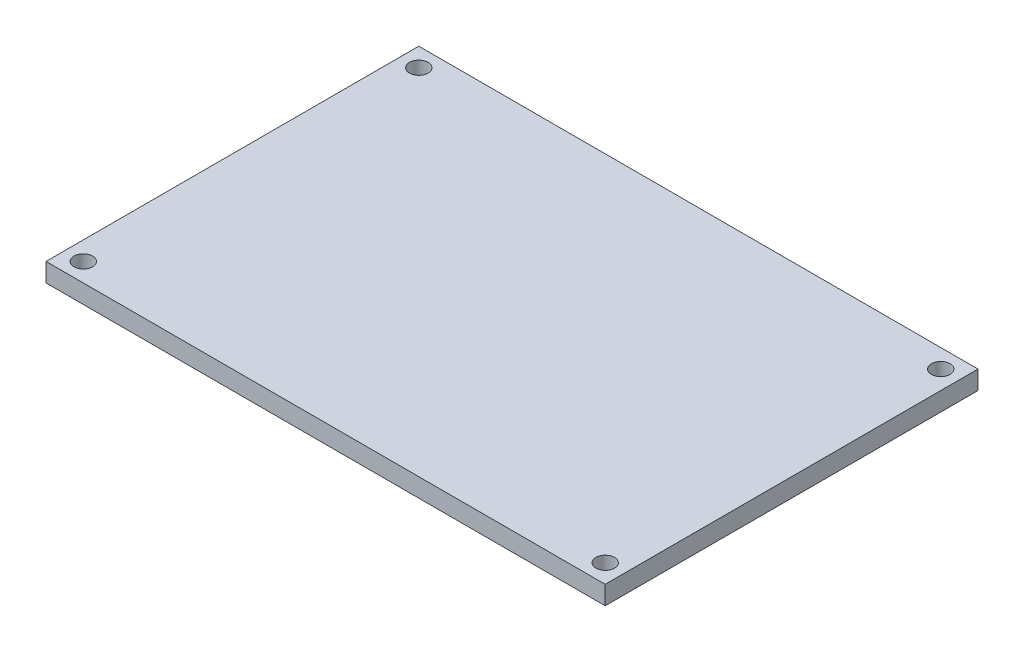
SolidWorks part; units mm, degrees
ref_plane "Front Plane" through (0, 0, 0) normal (0, 0, 1) x (1, 0, 0)
ref_plane "Top Plane" through (0, 0, 0) normal (0, 1, 0) x (1, 0, 0)
ref_plane "Right Plane" through (0, 0, 0) normal (1, 0, 0) x (0, 0, -1)
sketch "Sketch1" plane through (0, 0, 0) normal (0, 1, 0) x (1, 0, 0)
  line L1 (0, 0) -> (60, 0)
  line L2 (0, 0) -> (0, 40)
  line L3 (0, 40) -> (60, 40)
  line L4 (60, 0) -> (60, 40)
  dimension "D1" = 60
  dimension "D2" = 40
extrude "Boss-Extrude1" add sketch "Sketch1" along normal blind 2
sketch "Sketch2" plane through (0, 2, 0) normal (0, 1, 0) x (1, 0, 0)
  line L0 (60, 40) -> (0, 40) construction
  line L1 (0, 40) -> (0, 0) construction
  line L2 (60, 0) -> (60, 40) construction
  line L3 (2, 38) -> (58, 38) construction
  line L4 (2, 38) -> (2, 2) construction
  line L5 (2, 2) -> (58, 2) construction
  line L6 (58, 38) -> (58, 2) construction
  line L7 (0, 0) -> (60, 0) construction
  circle A0 centre (2, 38) radius 1
  circle A1 centre (2, 2) radius 1
  circle A2 centre (58, 2) radius 1
  circle A3 centre (58, 38) radius 1
  dimension "D1" = 2
  dimension "D2" = 2
  dimension "D3" = 2
  dimension "D4" = 2
  dimension "D5" = 2
extrude "Cut-Extrude1" cut sketch "Sketch2" against normal through all
